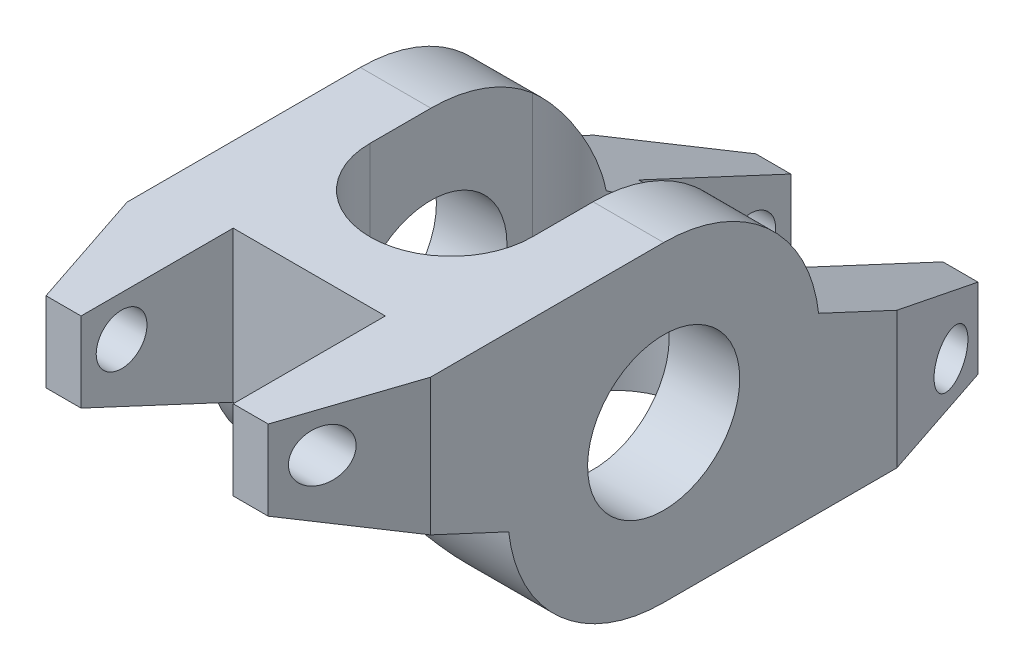
SolidWorks part; units mm, degrees
ref_plane "Front Plane" through (0, 0, 0) normal (0, 0, 1) x (1, 0, 0)
ref_plane "Top Plane" through (0, 0, 0) normal (0, 1, 0) x (1, 0, 0)
ref_plane "Right Plane" through (0, 0, 0) normal (1, 0, 0) x (0, 0, -1)
sketch "Sketch1" plane through (0, 0, 0) normal (1, 0, 0) x (0, 0, -1)
  line L0 (0, 9.765) -> (-22.23, 9.765)
  line L1 (-22.23, 9.765) -> (-22.23, 4.765)
  line L2 (-22.23, 4.765) -> (-9.7056, -1.0752)
  line L3 (0, -9.765) -> (22.23, -9.765)
  line L4 (22.23, -9.765) -> (22.23, -4.765)
  line L5 (22.23, -4.765) -> (9.7056, 1.0752)
  circle A0 centre (0, 0) radius 4.765
  arc A1 (-9.7056, -1.0752) -> (0, -9.765) centre (0, 0) ccw
  circle A2 centre (0, 0) radius 9.765 construction
  arc A3 (9.7056, 1.0752) -> (0, 9.765) centre (0, 0) ccw
  dimension "D1" = 9.53
  dimension "D9" = 5
  dimension "D3" = 22.23
  dimension "D4" = 5
  dimension "D5" = 25
  dimension "D6" = 22.23
  dimension "D7" = 5
  dimension "D8" = 25
  dimension "D2" = 5
extrude "Boss-Extrude1" add sketch "Sketch1" along normal mid plane 19
chamfer "Chamfer1" distance 2.54 distance2 7.62 2 edges at (9.5, 7.265, 22.23) (9.5, -7.265, -22.23)
chamfer "Chamfer2" distance 7.62 distance2 2.54 2 edges at (-9.5, 7.265, 22.23) (-9.5, -7.265, -22.23)
sketch "Sketch2" plane through (0, 0, 0) normal (0, 1, 0) x (1, 0, 0)
  line L0 (0, -3.81) -> (0, 6.35) construction
  line L1 (-5.08, -3.81) -> (-5.08, 6.35)
  line L2 (5.08, -3.81) -> (5.08, 6.35)
  arc A0 (-5.08, -3.81) -> (5.08, -3.81) centre (0, -3.81) ccw
  arc A1 (5.08, 6.35) -> (-5.08, 6.35) centre (0, 6.35) ccw
  point P3 (0, 1.27)
  dimension "D1" = 10.16
  dimension "D2" = 10.16
  dimension "D3" = 3.81
extrude "Cut-Extrude1" cut sketch "Sketch2" against normal through all both and the other way through all
sketch "Sketch3" plane through (0, 0, 0) normal (0, 1, 0) x (1, 0, 0)
  line L1 (6.96, 22.23) -> (-6.96, 22.23) construction
  line L2 (-4.765, 22.23) -> (4.765, 22.23)
  line L3 (-4.765, 22.23) -> (-4.765, 12.7)
  line L4 (-4.765, 12.7) -> (4.765, 12.7)
  line L5 (4.765, 22.23) -> (4.765, 12.7)
  line L7 (6.96, -22.23) -> (-6.96, -22.23) construction
  line L8 (-4.765, -12.7) -> (4.765, -12.7)
  line L9 (-4.765, -12.7) -> (-4.765, -22.23)
  line L10 (-4.765, -22.23) -> (4.765, -22.23)
  line L11 (4.765, -12.7) -> (4.765, -22.23)
  line L12 (-4.765, -12.7) -> (4.765, -22.23) construction
  line L13 (-4.765, -22.23) -> (4.765, -12.7) construction
  point P7 (0, -17.465)
  dimension "D1" = 9.53
  dimension "D2" = 9.53
  dimension "D3" = 9.53
  dimension "D4" = 9.53
extrude "Cut-Extrude2" cut sketch "Sketch3" against normal through all both and the other way through all
sketch "Sketch4" plane through (0, 0, 0) normal (1, 0, 0) x (0, 0, -1)
  line L2 (-22.23, 9.765) -> (-14.61, 9.765) construction
  line L3 (-22.23, 4.765) -> (-22.23, 9.765) construction
  line L4 (22.23, -4.765) -> (22.23, -9.765) construction
  line L5 (22.23, -9.765) -> (14.61, -9.765) construction
  circle A0 centre (-19.69, 7.225) radius 1.59
  circle A1 centre (19.69, -7.225) radius 1.59
  dimension "D1" = 3.18
  dimension "D2" = 3.18
  dimension "D3" = 2.54
  dimension "D4" = 2.54
  dimension "D5" = 2.54
  dimension "D7" = 2.54
extrude "Cut-Extrude3" cut sketch "Sketch4" against normal through all both and the other way through all
